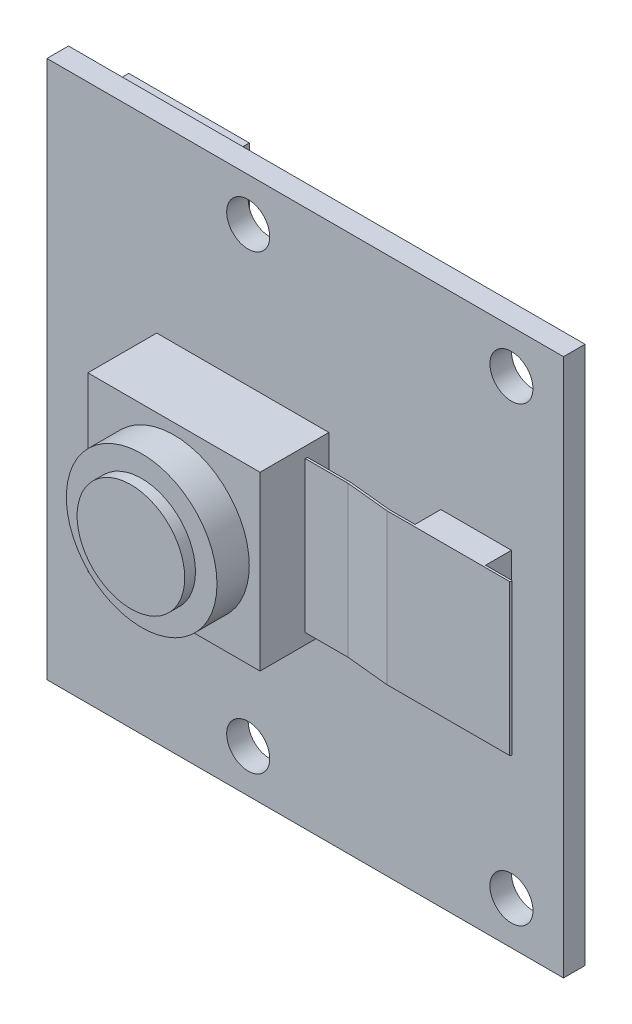
SolidWorks part; units mm, degrees
ref_plane "Alzado" through (0, 0, 0) normal (0, 0, 1) x (1, 0, 0)
ref_plane "Planta" through (0, 0, 0) normal (0, 1, 0) x (1, 0, 0)
ref_plane "Vista lateral" through (0, 0, 0) normal (1, 0, 0) x (0, 0, -1)
sketch "Croquis1" plane through (0, 0, 0) normal (0, 0, 1) x (1, 0, 0)
  line L0 (-12, 0) -> (12, 0) construction
  line L1 (12, -12.5) -> (-12, -12.5)
  line L2 (12, -12.5) -> (12, 12.5)
  line L3 (12, 12.5) -> (-12, 12.5)
  line L4 (-12, -12.5) -> (-12, 12.5)
  line L5 (12, -12.5) -> (-12, 12.5) construction
  line L6 (12, 12.5) -> (-12, -12.5) construction
  circle A0 centre (9.58, -10.5) radius 1
  circle A1 centre (-2.65, -10.5) radius 1
  circle A2 centre (9.58, 10.5) radius 1
  circle A3 centre (-2.65, 10.5) radius 1
  point P0 (0, 0)
  dimension "D3" = 2
  dimension "D6" = 2
  dimension "D1" = 25
  dimension "D2" = 24
  dimension "D4" = 9.35
  dimension "D5" = 21.58
extrude "Saliente-Extruir1" add sketch "Croquis1" along normal blind 1
sketch "Croquis2" plane through (0, 0, 1) normal (0, 0, 1) x (1, 0, 0)
  line L0 (-12.1201, 0) -> (12, 0) construction
  line L1 (12, -12.5) -> (12, 12.5) construction
  line L2 (-12, 12.5) -> (-12, -12.5) construction
  line L3 (1.1, -4) -> (-6.9, -4)
  line L4 (1.1, -4) -> (1.1, 4)
  line L5 (1.1, 4) -> (-6.9, 4)
  line L6 (-6.9, -4) -> (-6.9, 4)
  line L7 (1.1, -4) -> (-6.9, 4) construction
  line L8 (1.1, 4) -> (-6.9, -4) construction
  point P4 (-2.9, 0)
  dimension "D1" = 8
  dimension "D2" = 5.1
extrude "Saliente-Extruir2" add sketch "Croquis2" along normal blind 5.2
sketch "Croquis3" plane through (0, 0, 6.2) normal (0, 0, 1) x (1, 0, 0)
  line L0 (-6.9, 4) -> (1.1, -4) construction
  line L2 (1.1, -4) -> (-6.9, -4)
  line L3 (1.1, -4) -> (1.1, 4)
  line L4 (1.1, 4) -> (-6.9, 4)
  line L5 (-6.9, -4) -> (-6.9, 4)
  line L6 (1.1, -4) -> (-6.9, 4) construction
  line L7 (1.1, 4) -> (-6.9, -4) construction
  circle A0 centre (-2.9, 0) radius 3.5
  line M6 (-6.9, 4) -> (-6.9, -4)
  line M7 (-6.9, -4) -> (1.1, -4)
  line M8 (1.1, -4) -> (1.1, 4)
  line M9 (1.1, 4) -> (-6.9, 4)
  dimension "D1" = 7
extrude "Cortar-Extruir1" cut sketch "Croquis3" against normal blind 2 contours A0 M9 M6 M7 M8 | L3 L2 L5 L4
sketch "Croquis4" plane through (0, 0, 6.2) normal (0, 0, 1) x (1, 0, 0)
  circle A0 centre (-2.9, 0) radius 2.5
  circle A1 centre (-2.9, 0) radius 3.5 construction
  circle A2 centre (-2.9, 0) radius 3.5
  dimension "D1" = 1
extrude "Cortar-Extruir2" cut sketch "Croquis4" against normal blind 0.5
sketch "Croquis5" plane through (0, 0, 0) normal (0, 1, 0) x (1, 0, 0)
  line L0 (1.1, -2) -> (3.1, -2)
  line L1 (3.1, -2) -> (5.1, -2.2)
  line L2 (5.1, -2.2) -> (10.78, -2.2)
  line L3 (8.58, -1) -> (10.58, -1) construction
  line L4 (-6.9, -4.2) -> (1.1, -4.2)
  line L5 (1.1, -4.2) -> (1.1, -1)
  line L6 (1.1, -1) -> (-6.9, -1)
  line L7 (-6.9, -1) -> (-6.9, -4.2)
  line L8 (-6.9, -4.2) -> (1.1, -4.2)
  line L9 (1.1, -4.2) -> (1.1, -1)
  line L10 (1.1, -1) -> (-6.9, -1)
  line L11 (-6.9, -1) -> (-6.9, -4.2)
  line L12 (12, 0) -> (-12, 0)
  line L13 (-12, 0) -> (-12, -1)
  line L14 (-12, -1) -> (12, -1)
  line L15 (12, -1) -> (12, 0)
  line L16 (12, 0) -> (-12, 0)
  line L17 (-12, 0) -> (-12, -1)
  line L19 (12, -1) -> (12, 0)
  line L20 (8.58, -1) -> (10.58, -1)
  line L21 (1.1, -2.1) -> (3.095, -2.1)
  line L22 (9.58, -1) -> (6.3, -1)
  line L23 (9.58, -1) -> (9.58, -2.2)
  line L24 (9.58, -2.2) -> (6.3, -2.2)
  line L25 (6.3, -1) -> (6.3, -2.2)
  line L26 (3.095, -2.1) -> (5.095, -2.3)
  line L27 (5.095, -2.3) -> (10.78, -2.3)
  arc A0 (1.1, -2) -> (1.1, -2.1) centre (1.1, -2.05) ccw
  arc A1 (10.78, -2.2) -> (10.78, -2.3) centre (10.78, -2.25) cw
  point P24 (0, 0)
  point P25 (0, 0)
  point P26 (0, 0)
  dimension "D3" = 0.2
  dimension "D4" = 4
  dimension "D5" = 1.2
  dimension "D6" = 2
  dimension "D7" = 1.2
  dimension "D8" = 1.2
  dimension "D1" = 0
  dimension "D2" = 0
  dimension "D9" = 0.1
extrude "Saliente-Extruir3" add sketch "Croquis5" along normal blind 3.5 and the other way blind 3.5 contours L22 L25 L2 L23 L20 | A1 L2 L1 L0 L9 L21 L26 L27
sketch "Croquis6" plane through (0, 0, 0) normal (0, 0, -1) x (-1, 0, 0)
  line L0 (-12, 0) -> (12, 0) construction
  line L1 (-12, -12.5) -> (-12, 12.5) construction
  line L2 (12, 12.5) -> (12, -12.5) construction
  line L4 (12, -10) -> (6.4, -10)
  line L5 (12, -10) -> (12, 10)
  line L6 (12, 10) -> (6.4, 10)
  line L7 (6.4, -10) -> (6.4, 10)
  line L8 (12, -10) -> (6.4, 10) construction
  line L9 (12, 10) -> (6.4, -10) construction
  point P6 (9.2, 0)
  dimension "D1" = 5.6
  dimension "D2" = 20
extrude "Saliente-Extruir4" add sketch "Croquis6" along normal blind 2.8
